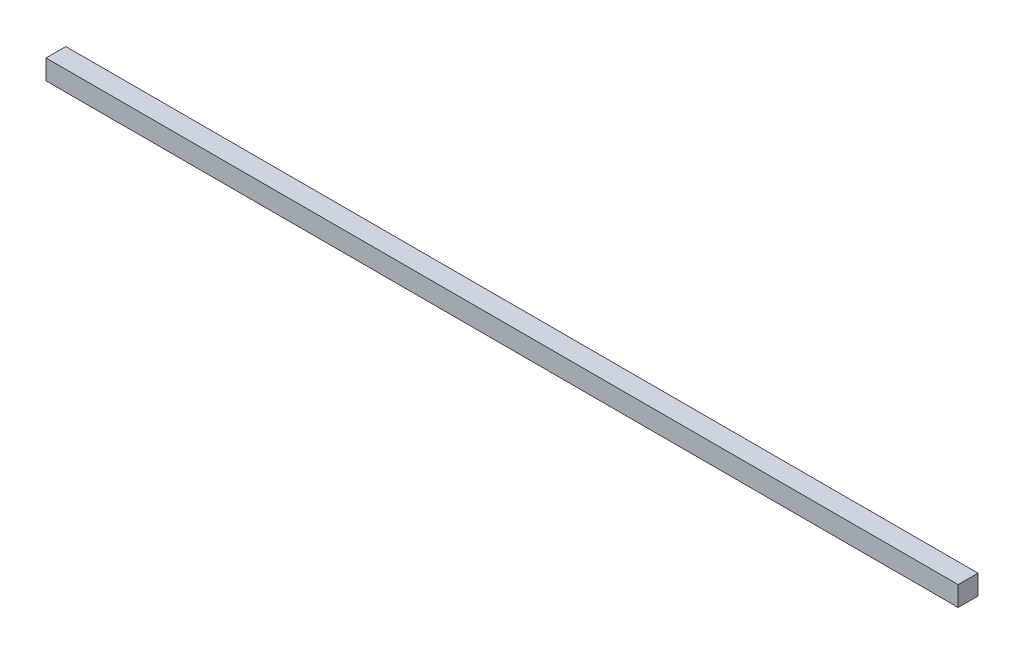
SolidWorks part; units mm, degrees
ref_plane "Front Plane" through (0, 0, 0) normal (0, 0, 1) x (1, 0, 0)
ref_plane "Top Plane" through (0, 0, 0) normal (0, 1, 0) x (1, 0, 0)
ref_plane "Right Plane" through (0, 0, 0) normal (1, 0, 0) x (0, 0, -1)
sketch "Sketch1" plane through (0, 0, 0) normal (1, 0, 0) x (0, 0, -1)
  line L1 (-12.7, 12.7) -> (12.7, 12.7)
  line L2 (-12.7, 12.7) -> (-12.7, -12.7)
  line L3 (-12.7, -12.7) -> (12.7, -12.7)
  line L4 (12.7, 12.7) -> (12.7, -12.7)
  line L5 (-12.7, 12.7) -> (12.7, -12.7) construction
  line L6 (-12.7, -12.7) -> (12.7, 12.7) construction
  point P0 (0, 0)
  point P6 (0, -12.7)
  dimension "D1" = 25.4
extrude "Boss-Extrude1" add sketch "Sketch1" along normal blind 1168.4
